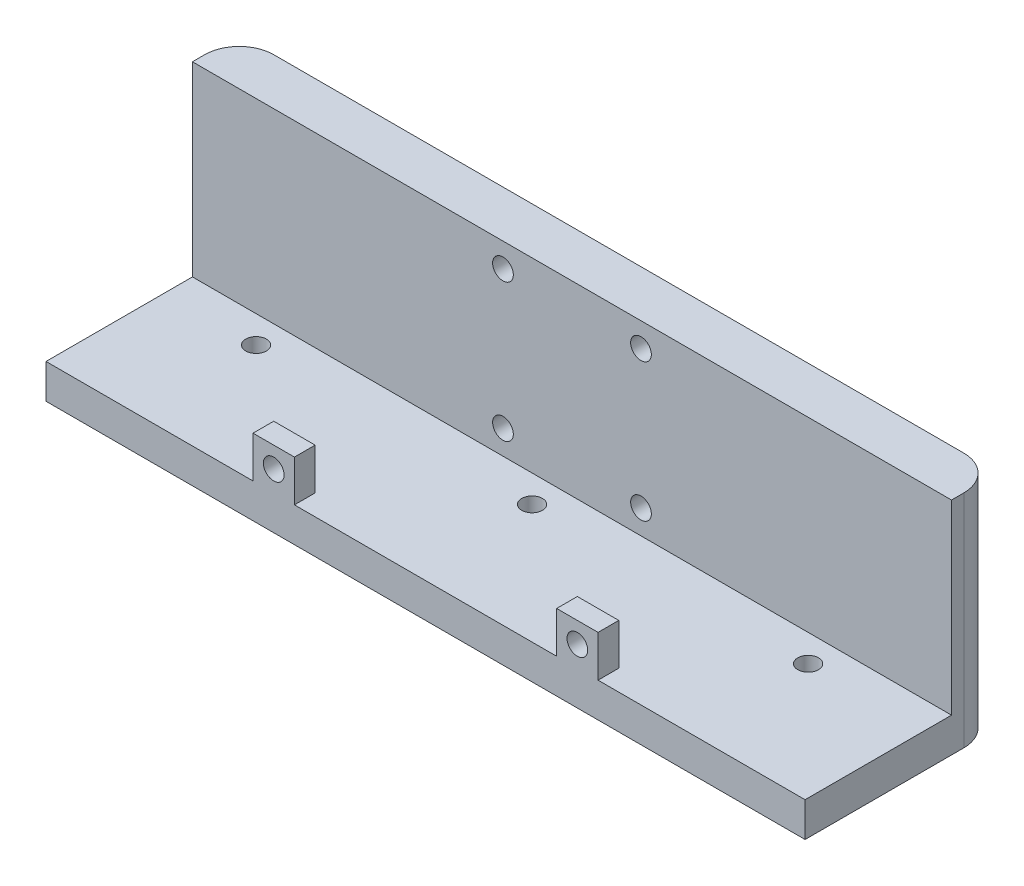
SolidWorks part; units mm, degrees
ref_plane "Front Plane" through (0, 0, 0) normal (0, 0, 1) x (1, 0, 0)
ref_plane "Top Plane" through (0, 0, 0) normal (0, 1, 0) x (1, 0, 0)
ref_plane "Right Plane" through (0, 0, 0) normal (1, 0, 0) x (0, 0, -1)
sketch "Sketch1" plane through (0, 0, 0) normal (0, 1, 0) x (1, 0, 0)
  line L1 (0, 0) -> (110, 0)
  line L2 (0, 0) -> (0, 28)
  line L3 (0, 28) -> (110, 28)
  line L4 (110, 0) -> (110, 28)
  dimension "D1" = 110
  dimension "D2" = 28
extrude "Boss-Extrude1" add sketch "Sketch1" along normal blind 5
sketch "Sketch2" plane through (0, 0, -28) normal (0, 0, -1) x (-1, 0, 0)
  line L1 (-110, 0) -> (0, 0)
  line L2 (-110, 0) -> (-110, 32)
  line L3 (-110, 32) -> (0, 32)
  line L4 (0, 0) -> (0, 32)
  dimension "D1" = 32
extrude "Boss-Extrude2" add sketch "Sketch2" against normal blind 6.78
sketch "Sketch3" plane through (0, 5, 0) normal (0, 1, 0) x (-1, 0, 0)
  line L0 (0, 0) -> (-110, 0) construction
  line L1 (0, -21.22) -> (0, 0) construction
  circle A0 centre (-13.16, -17.28) radius 1.5
  circle A1 centre (-53.16, -17.28) radius 1.5
  circle A2 centre (-93.16, -17.28) radius 1.5
  dimension "D3" = 3
  dimension "D1" = 17.28
  dimension "D2" = 13.16
  dimension "D4" = 3
extrude "Cut-Extrude1" cut sketch "Sketch3" against normal through all
sketch "Sketch4" plane through (0, 0, -21.22) normal (0, 0, 1) x (1, 0, 0)
  line L0 (110, 5) -> (0, 5) construction
  line L1 (0, 5) -> (0, 32) construction
  circle A0 centre (45, 8.5) radius 1.5
  circle A1 centre (65, 8.5) radius 1.5
  circle A2 centre (45, 28.5) radius 1.5
  circle A3 centre (65, 28.5) radius 1.5
  dimension "D1" = 3
  dimension "D2" = 3.5
  dimension "D5" = 45
  dimension "D3" = 2
  dimension "D4" = 2
extrude "Cut-Extrude2" cut sketch "Sketch4" against normal through all
fillet "Fillet1" radius 5 2 edges at (0, 16, -28) (110, 16, -28)
sketch "Sketch5" plane through (0, 5, 0) normal (0, 1, 0) x (-1, 0, 0)
  line L0 (0, 0) -> (-110, 0) construction
  line L1 (-30, 0) -> (-36, 0)
  line L2 (-30, 0) -> (-30, -3)
  line L3 (-30, -3) -> (-36, -3)
  line L4 (-36, 0) -> (-36, -3)
  line L5 (-110, 0) -> (-110, -21.22) construction
  line L6 (-74, 0) -> (-80, 0)
  line L7 (-74, 0) -> (-74, -3)
  line L8 (-74, -3) -> (-80, -3)
  line L9 (-80, 0) -> (-80, -3)
  line L10 (0, -21.22) -> (0, 0) construction
  dimension "D1" = 3
  dimension "D2" = 6
  dimension "D3" = 3
  dimension "D4" = 6
  dimension "D5" = 30
  dimension "D6" = 30
extrude "Boss-Extrude3" add sketch "Sketch5" along normal blind 6
sketch "Sketch6" plane through (0, 0, 0) normal (0, 0, 1) x (1, 0, 0)
  line L0 (30, 11) -> (30, 5) construction
  line L2 (30, 11) -> (36, 11) construction
  line L3 (74, 11) -> (80, 11) construction
  line L4 (80, 11) -> (80, 5) construction
  circle A0 centre (33, 8) radius 1.5
  circle A1 centre (77, 8) radius 1.5
  dimension "D1" = 3
  dimension "D4" = 3
  dimension "D6" = 3
  dimension "D2" = 3
  dimension "D3" = 3
  dimension "D5" = 3
extrude "Cut-Extrude3" cut sketch "Sketch6" against normal blind 6
